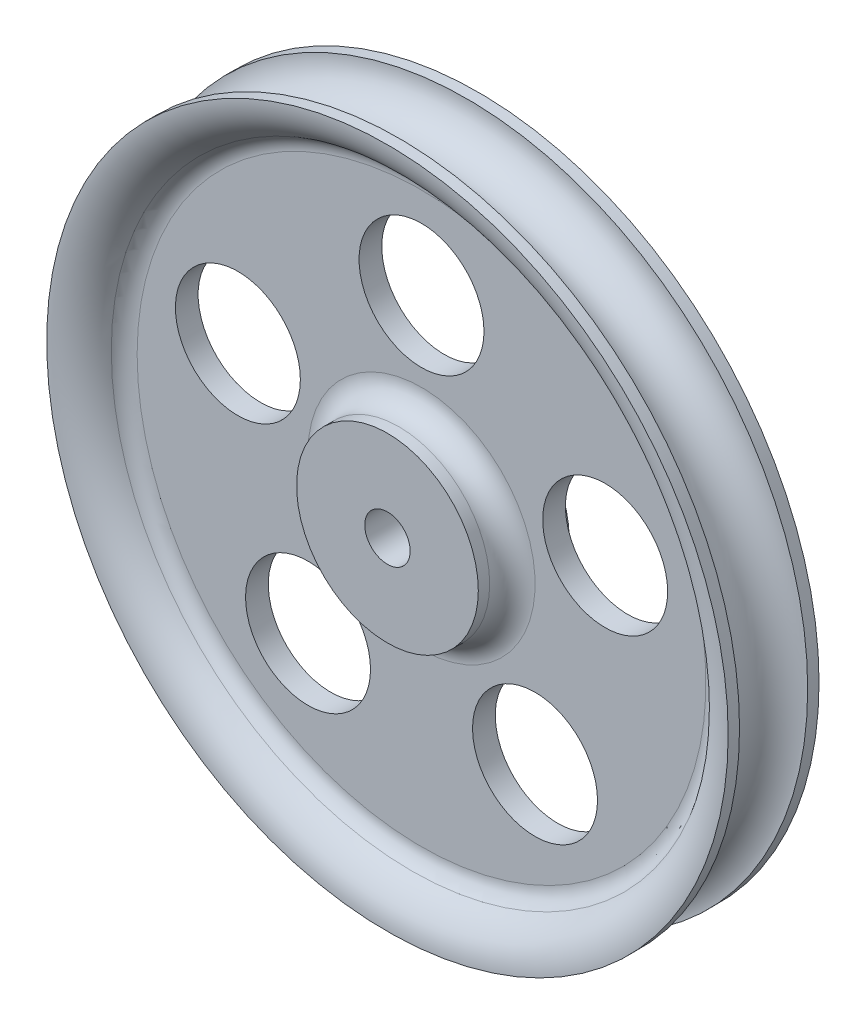
SolidWorks part; units mm, degrees
material "6063-T6"
ref_plane "Front Plane" through (0, 0, 0) normal (0, 0, 1) x (1, 0, 0)
ref_plane "Top Plane" through (0, 0, 0) normal (0, 1, 0) x (1, 0, 0)
ref_plane "Right Plane" through (0, 0, 0) normal (1, 0, 0) x (0, 0, -1)
sketch "Sketch1" plane through (0, 0, 0) normal (1, 0, 0) x (0, 0, -1)
  line L0 (0, 190.5) -> (0, -168.1789) construction
  line L1 (-136.6527, 0) -> (122.9861, 0) construction
  line L2 (-19.05, 190.5) -> (-25.4, 190.5)
  line L3 (19.05, 190.5) -> (25.4, 190.5)
  line L4 (-25.4, 12.7) -> (25.4, 12.7)
  line L5 (25.4, 12.7) -> (25.4, 50.8)
  line L6 (-25.4, 12.7) -> (-25.4, 50.8)
  line L7 (25.4, 50.8) -> (6.35, 50.8)
  line L8 (-25.4, 50.8) -> (-6.35, 50.8)
  line L9 (6.35, 50.8) -> (6.35, 165.9066)
  line L10 (-6.35, 50.8) -> (-6.35, 165.9066)
  arc A0 (-19.05, 190.5) -> (19.05, 190.5) centre (0, 190.5) ccw
  arc A1 (-25.4, 190.5) -> (-6.35, 165.9066) centre (0, 190.5) ccw
  arc A2 (6.35, 165.9066) -> (25.4, 190.5) centre (0, 190.5) ccw
  point P12 (0, 12.7)
  dimension "D1" = 50.8
  dimension "D2" = 38.1
  dimension "D3" = 381
  dimension "D4" = 25.4
  dimension "D5" = 101.6
  dimension "D6" = 50.8
  dimension "D7" = 12.7
revolve "Revolve1" add sketch "Sketch1" angle 360 about L1
sketch "Sketch2" plane through (0, 0, 6.35) normal (0, 0, 1) x (1, 0, 0)
  circle A0 centre (0, 0) radius 107.95 construction
  circle A1 centre (0, 107.95) radius 34.925
  dimension "D1" = 215.9
  dimension "D2" = 69.85
extrude "Cut-Extrude1" cut sketch "Sketch2" against normal through all
pattern_circular "CirPattern1" count 5 over 360 about axis through (0, 0, 0) along (0, 0, 1) of "Cut-Extrude1"
fillet "Fillet1" radius 10.16 2 edges at (165.9066, 0, -6.35) (165.9066, 0, 6.35)
fillet "Fillet2" radius 12.7 2 edges at (50.8, 0, 6.35) (50.8, 0, -6.35)
